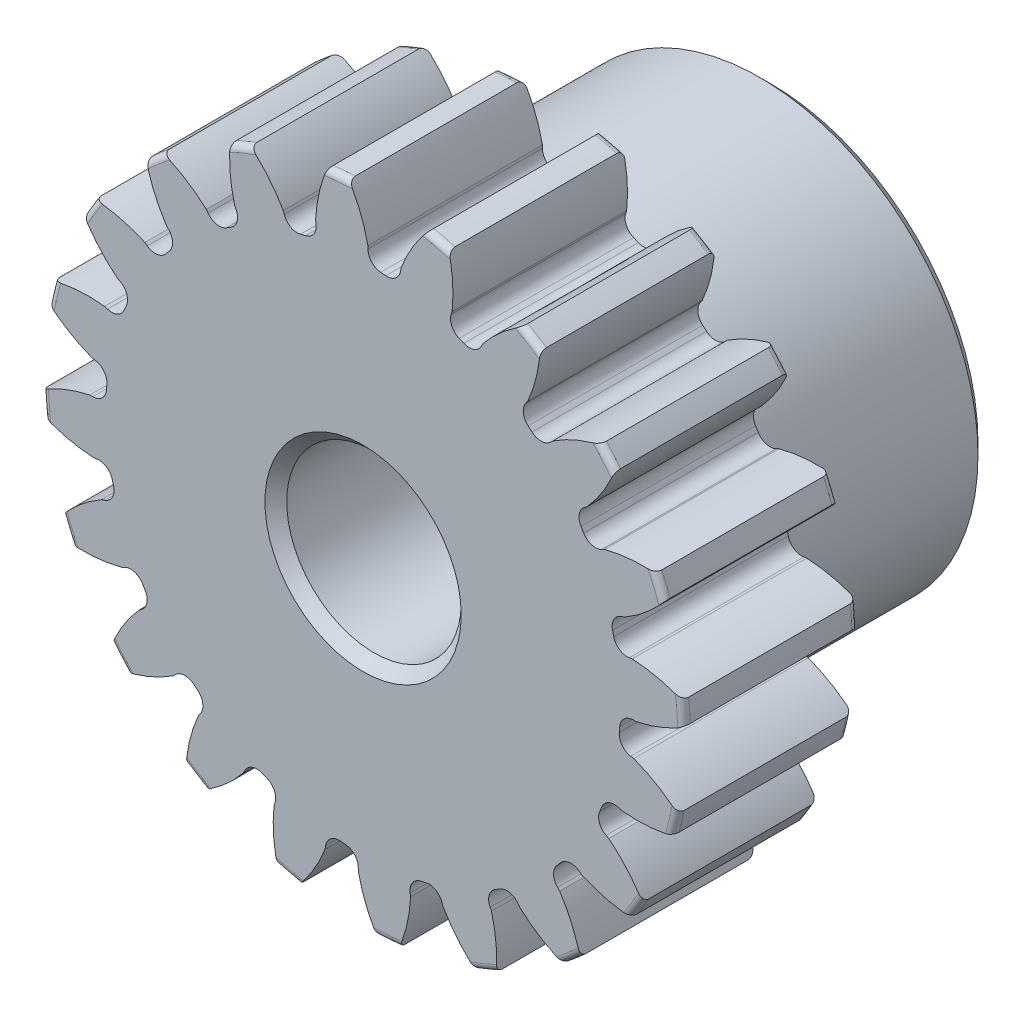
SolidWorks part; units mm, degrees
ref_plane "Front" through (0, 0, 0) normal (0, 0, 1) x (1, 0, 0)
ref_plane "Top" through (0, 0, 0) normal (0, 1, 0) x (1, 0, 0)
ref_plane "Right" through (0, 0, 0) normal (1, 0, 0) x (0, 0, -1)
sketch "Sketch1" plane through (0, 0, 0) normal (0, 0, 1) x (1, 0, 0)
  line L0 (-254, 0) -> (254, 0) construction
  circle A0 centre (0, 0) radius 8.763
  circle A1 centre (0, 0) radius 7.9375 construction
  circle A3 centre (0, 0) radius 7.0191 construction
  dimension "D1" = 0.9184
  dimension "D2" = 1.7439
  dimension "D3" = 0.8255
extrude "Boss-Extrude1" add sketch "Sketch1" against normal blind 4.7625
sketch "Sketch2" plane through (0, 0, 0) normal (1, 0, 0) x (0, 0, -1)
  line L0 (4.7625, 0) -> (11.1252, 0)
  line L1 (4.7625, 0) -> (4.7625, 5.9531)
  line L2 (4.7625, 5.9531) -> (11.1252, 5.9531)
  line L3 (11.1252, 5.9531) -> (11.1252, 0)
  point P5 (11.1252, -5.9531)
  point P6 (0, -8.763)
  point P7 (4.7625, -8.763)
  point P9 (0, 8.763)
revolve "Revolve1" add sketch "Sketch2" angle 360 mid plane about L0
fillet "Fillet2" radius 0.1753 3 edges at (8.763, 0, -4.7625) (8.763, 0, 0) (5.9531, 0, -4.7625)
sketch "Sketch3" plane through (0, 0, 0) normal (0, 0, 1) x (1, 0, 0)
  line L0 (0, 0) -> (0, 8.763) construction
  line L1 (-2.5511, 7.009) -> (0, 7.9375)
  line L2 (-9.5921, 7.9375) -> (9.5921, 7.9375) construction
  line L3 (-9.0136, 4.6568) -> (9.0136, 11.2182) construction
  line L4 (-2.5511, 7.009) -> (0, 0) construction
  line L5 (-6.2194, 4.1174) -> (0, 0) construction
  line L6 (-6.2194, 4.1174) -> (-2.0982, 10.3425) construction
  line L7 (-1.7721, 7.2452) -> (0, 0) construction
  line L8 (-1.7721, 7.2452) -> (0.0739, 7.6967) construction
  arc A0 (-2.5511, 7.009) -> (-6.2194, 4.1174) centre (0, 0) ccw
  circle A1 centre (0, 0) radius 7.9375 construction
  circle A2 centre (0, 0) radius 7.4588 construction
  arc A3 (-2.5511, 7.009) -> (-1.7721, 7.2452) centre (0, 0) cw
  circle A4 centre (0, 0) radius 8.763 construction
  point P6 (0, 7.9375)
  dimension "D1" = 2.7148
  dimension "D3" = 7.4657
  dimension "D5" = 1.9003
  dimension "D2" = 4.7509
  dimension "D4" = 0.8144
sketch "Sketch4" plane through (0, 0, 0) normal (0, 0, 1) x (1, 0, 0)
  line L0 (0, 0) -> (0.6209, 7.8886) construction
  line L1 (0.1318, 7.4576) -> (0.1318, 7.0179)
  line L2 (0, 7.9375) -> (1.2417, 7.8398) construction
  line L3 (1.0365, 7.3864) -> (0.9677, 6.9521)
  line L4 (0.1318, 7.0179) -> (0, 0) construction
  line L5 (0, 0) -> (0, 8.763) construction
  line L6 (-6.2194, 4.1174) -> (-2.0982, 10.3425) construction
  line L7 (-6.2194, 4.1174) -> (-2.0982, 10.3425) construction
  arc A0 (0.9677, 6.9521) -> (0.1318, 7.0179) centre (0, 0) ccw
  arc A1 (0, 7.9375) -> (1.2417, 7.8398) centre (0, 0) cw construction
  circle A2 centre (0, 0) radius 7.9375 construction
  circle A3 centre (0, 0) radius 7.4588 construction
  circle A4 centre (0, 0) radius 7.0191 construction
  arc A5 (3.6903, 9.8869) -> (-2.0982, 10.3425) centre (0, 0) ccw
  spline S0 degree 2 poles (-2.0982, 10.3425) (-0.2509, 9.2652) (0.1318, 7.4576) knots 0 0 0 1 1 1
  spline S1 degree 2 poles (3.6903, 9.8869) (1.6972, 9.1118) (1.0365, 7.3864) knots 0 0 0 1 1 1
  dimension "D1" = 1.2468
extrude "Cut-Extrude1" cut sketch "Sketch4" against normal through all
fillet "Fillet1" radius 0.374 2 edges at (0.9677, 6.9521, -2.3813) (0.1318, 7.0179, -2.3813)
pattern_circular "CirPattern1" count 20 over 360 about axis through (0, 0, -4.7625) along (0, 0, 1) of "Cut-Extrude1", "Fillet1"
sketch "Sketch5" plane through (0, 0, 0) normal (0, 0, 1) x (1, 0, 0)
  circle A0 centre (0, 0) radius 2.3813
  circle A1 centre (0, 0) radius 2.3813 construction
  dimension "Bore Min" = 4.7625
  dimension "Bore Max" = 4.7625
extrude "Cut-Extrude2" cut sketch "Sketch5" against normal through all
chamfer "Chamfer1" distance 0.2977 angle 45 3 edges at (5.9531, 0, -11.1252) (2.3813, 0, 0) (2.3813, 0, -11.1252)
sketch "Pitch Dia" plane through (0, 0, 0) normal (0, 0, 1) x (1, 0, 0)
  circle A0 centre (0, 0) radius 7.9375 construction
  circle A1 centre (0, 0) radius 7.9375 construction
equation "\"D1@Boss-Extrude1\" = \"Face Wd@Sketch2\""
equation "\"D2@Sketch3\" = \"D1@Sketch3\"*1.75"
equation "\"D3@Sketch3\" = \"D1@Sketch3\"+\"D2@Sketch3\""
equation "\"D4@Sketch3\" = \"D1@Sketch3\"*.3"
equation "\"D5@Sketch3\" = \"D1@Sketch3\"-\"D4@Sketch3\""
equation "\"D1@Sketch4\" = 1.5708/(\"Number of Teeth@Sketch1\"/\"Ptich Dia@Sketch1\")"
equation "\"D1@Chamfer1\" = \"B Hub Dia@Sketch2\"*.025"
equation "\"D1@CirPattern1\" = \"Number of Teeth@Sketch1\""
equation "\"D1@Fillet1\" = \"D1@Sketch4\"*.3"
equation "\"D1@Fillet2\" = \"OD@Sketch1\"*.01"
equation "\"D1@Sketch1\" = 1.157/(\"Number of Teeth@Sketch1\"/\"Ptich Dia@Sketch1\")"
